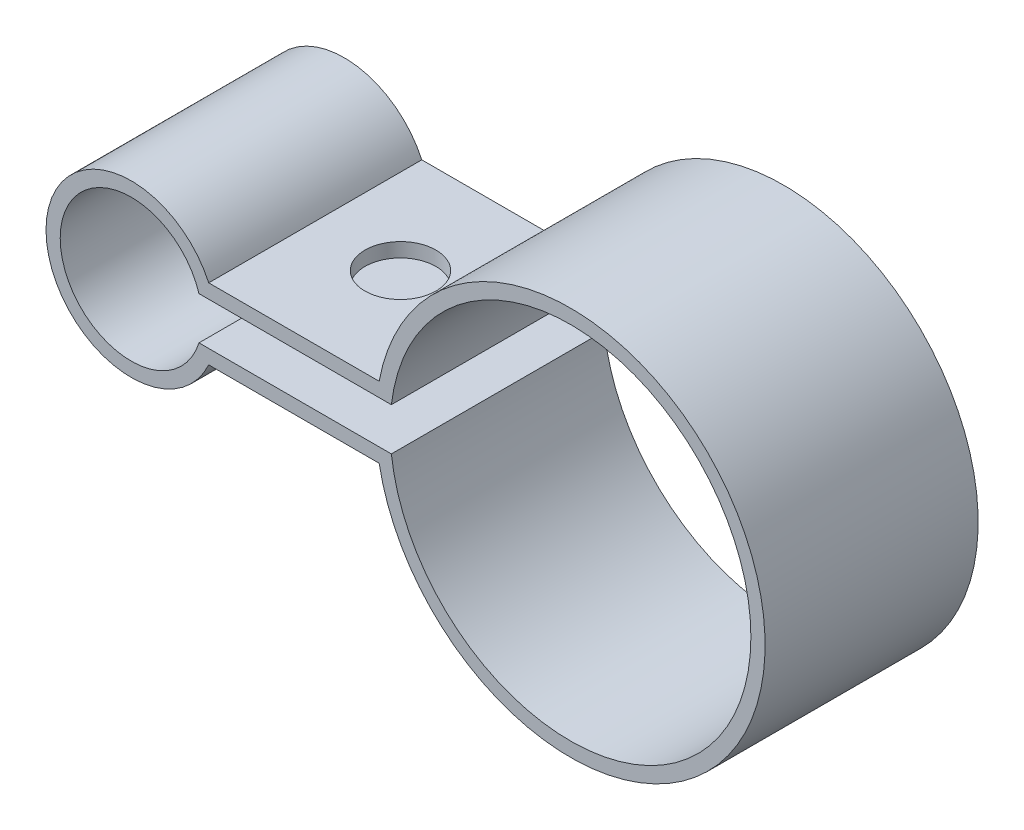
SolidWorks part; units mm, degrees
ref_plane "Alzado" through (0, 0, 0) normal (0, 0, 1) x (1, 0, 0)
ref_plane "Planta" through (0, 0, 0) normal (0, 1, 0) x (1, 0, 0)
ref_plane "Vista lateral" through (0, 0, 0) normal (1, 0, 0) x (0, 0, -1)
sketch "Croquis1" plane through (0, 0, 0) normal (0, 0, 1) x (1, 0, 0)
  line L0 (0, 0) -> (30.9243, 0) construction
  line L1 (0, 0) -> (0, 2.5) construction
  line L2 (0, 2.5) -> (30.9243, 2.5) construction
  line L3 (30.9243, 2.5) -> (30.9243, 0) construction
  line L4 (5.4544, 2.5) -> (17.4544, 2.5)
  line L6 (4.7697, 1.5) -> (18.3132, 1.5)
  line L7 (4.7697, -1.5) -> (9.5415, -1.5)
  line L8 (5.4544, -2.5) -> (9.5415, -2.5)
  line L11 (13.5415, -2.5) -> (17.4544, -2.5)
  line L12 (13.5415, -1.5) -> (18.3132, -1.5)
  line L13 (9.5415, -2.5) -> (13.5415, -2.5)
  line L14 (9.5415, -1.5) -> (13.5415, -1.5)
  arc A0 (4.7697, 1.5) -> (4.7697, -1.5) centre (0, 0) ccw
  arc A1 (5.4544, 2.5) -> (5.4544, -2.5) centre (0, 0) ccw
  arc A2 (18.3132, -1.5) -> (18.3132, 1.5) centre (30.9243, 0) ccw
  arc A3 (17.4544, -2.5) -> (17.4544, 2.5) centre (30.9243, 0) ccw
  point P7 (0, 0)
  point P15 (11.5415, -1.5)
  dimension "D1" = 10
  dimension "D2" = 12
  dimension "D3" = 13.7
  dimension "D4" = 25.4
  dimension "D5" = 1
  dimension "D6" = 12
  dimension "D7" = 30.9243
  dimension "D8" = 4
extrude "Saliente-Extruir1" add sketch "Croquis1" along normal blind 15
sketch "Croquis2" plane through (0, 2.5, 0) normal (0, 1, 0) x (1, 0, 0)
  line L0 (5.4544, 0) -> (17.4544, -15) construction
  circle A0 centre (11.4544, -7.5) radius 2.5
extrude "Cortar-Extruir1" cut sketch "Croquis2" against normal blind 15
